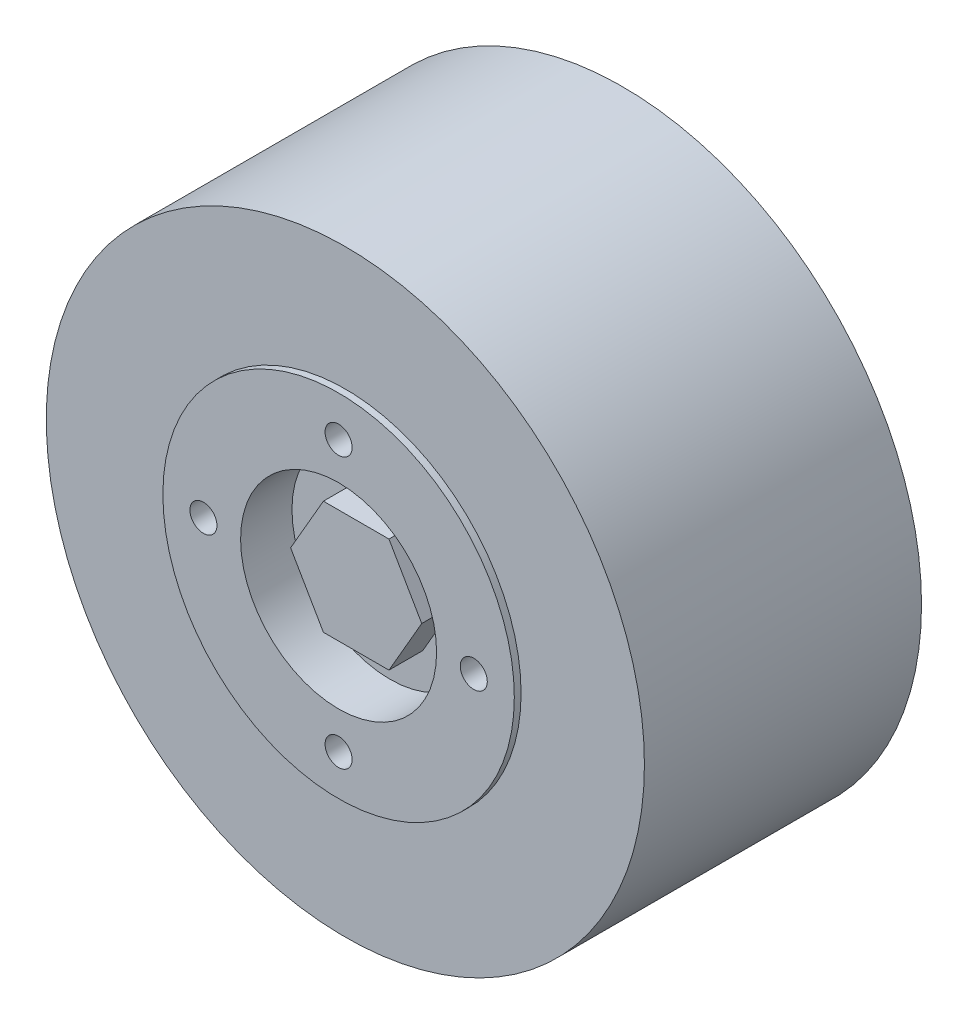
SolidWorks part; units mm, degrees
ref_plane "前视基准面" through (0, 0, 0) normal (0, 0, 1) x (1, 0, 0)
ref_plane "上视基准面" through (0, 0, 0) normal (0, 1, 0) x (1, 0, 0)
ref_plane "右视基准面" through (0, 0, 0) normal (1, 0, 0) x (0, 0, -1)
sketch "草图1" plane through (0, 0, 0) normal (0, 0, 1) x (1, 0, 0)
  circle A0 centre (0, 0) radius 44.25
  dimension "D1" = 88.5
extrude "凸台-拉伸1" add sketch "草图1" along normal blind 41 contours A0
sketch "草图2" plane through (0, 0, 41) normal (0, 0, 1) x (1, 0, 0)
  circle A0 centre (0, 0) radius 26
  dimension "D1" = 52
extrude "凸台-拉伸2" add sketch "草图2" along normal blind 1
sketch "草图3" plane through (0, 0, 42) normal (0, 0, 1) x (1, 0, 0)
  line L0 (-20, 0) -> (20, 0) construction
  line L1 (0, 20) -> (0, -20) construction
  circle A0 centre (0, 0) radius 20 construction
  circle A1 centre (0, 20) radius 2
  circle A2 centre (20, 0) radius 2
  circle A3 centre (0, -20) radius 2
  circle A4 centre (-20, 0) radius 2
  dimension "D1" = 40
  dimension "D2" = 4
  dimension "D3" = 4
  dimension "D4" = 4
  dimension "D5" = 4
extrude "切除-拉伸1" cut sketch "草图3" against normal blind 10
sketch "草图5" plane through (0, 0, 0) normal (0, 0, -1) x (-1, 0, 0)
  circle A0 centre (0, 0) radius 21
  dimension "D1" = 42
extrude "凸台-拉伸4" add sketch "草图5" along normal blind 1
sketch "草图6" plane through (0, 0, -1) normal (0, 0, -1) x (-1, 0, 0)
  line L0 (-15.5, 0) -> (15.5, 0) construction
  line L1 (0, 15.5) -> (0, -15.5) construction
  circle A0 centre (0, 0) radius 15.5 construction
  circle A1 centre (0, 15.5) radius 1.5
  dimension "D1" = 31
  dimension "D2" = 3
extrude "切除-拉伸2" cut sketch "草图6" against normal blind 10
pattern_circular "阵列(圆周)1" count 4 over 360 about axis through (0, 0, 0) along (0, 0, 1) of "切除-拉伸2"
sketch "草图7" plane through (0, 0, -1) normal (0, 0, -1) x (-1, 0, 0)
  circle A0 centre (0, 0) radius 1.5
  dimension "D1" = 3
extrude "凸台-拉伸5" add sketch "草图7" along normal blind 6
sketch "草图8" plane through (0, 0, 42) normal (0, 0, 1) x (1, 0, 0)
  circle A0 centre (0, 0) radius 14.5
  dimension "D1" = 29
extrude "切除-拉伸3" cut sketch "草图8" against normal blind 7.6
sketch "草图9" plane through (0, 0, 34.4) normal (0, 0, 1) x (1, 0, 0)
  line L1 (9.6995, 0) -> (4.8497, 8.4)
  line L2 (4.8497, 8.4) -> (-4.8497, 8.4)
  line L3 (-4.8497, 8.4) -> (-9.6995, 0)
  line L4 (-9.6995, 0) -> (-4.8497, -8.4)
  line L5 (-4.8497, -8.4) -> (4.8497, -8.4)
  line L6 (4.8497, -8.4) -> (9.6995, 0)
  circle A0 centre (0, 0) radius 8.4 construction
extrude "凸台-拉伸6" add sketch "草图9" along normal blind 5
